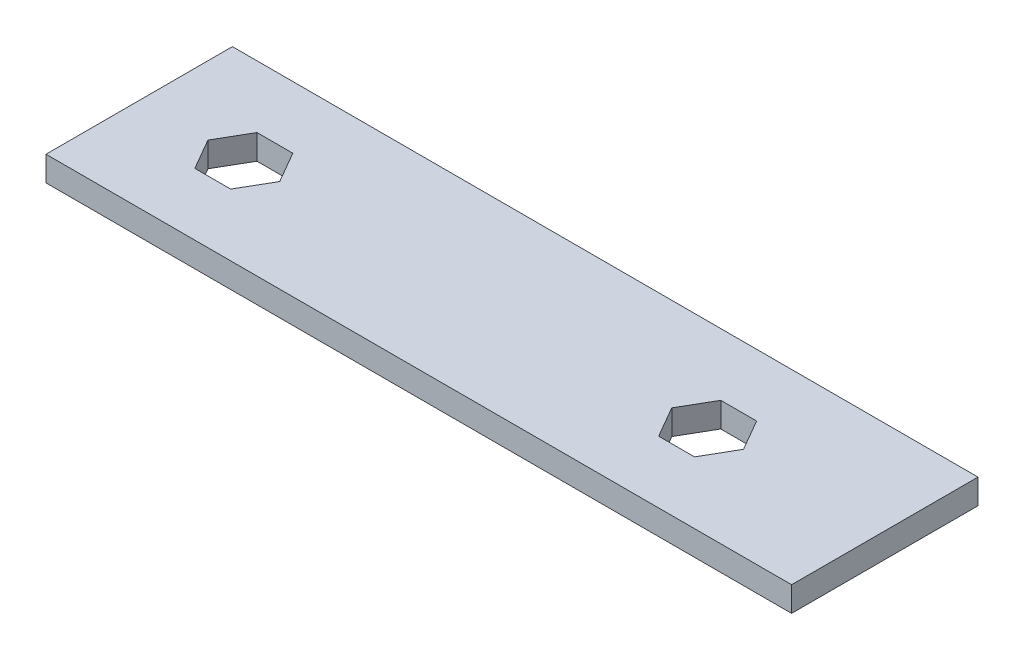
SolidWorks part; units mm, degrees
ref_plane "Front Plane" through (0, 0, 0) normal (0, 0, 1) x (1, 0, 0)
ref_plane "Top Plane" through (0, 0, 0) normal (0, 1, 0) x (1, 0, 0)
ref_plane "Right Plane" through (0, 0, 0) normal (1, 0, 0) x (0, 0, -1)
sketch "Sketch1" plane through (0, 0, 0) normal (0, 1, 0) x (1, 0, 0)
  line L1 (0, 0) -> (152.4, 0)
  line L2 (0, 0) -> (0, 38.1)
  line L3 (0, 38.1) -> (152.4, 38.1)
  line L4 (152.4, 0) -> (152.4, 38.1)
  dimension "D1" = 152.4
  dimension "D2" = 38.1
extrude "Boss-Extrude1" add sketch "Sketch1" along normal blind 5.08
sketch "Sketch2" plane through (0, 5.08, 0) normal (0, 1, 0) x (1, 0, 0)
  line L1 (25.0498, 12.7) -> (28.716, 19.05)
  line L2 (28.716, 19.05) -> (25.0498, 25.4)
  line L3 (25.0498, 25.4) -> (17.7175, 25.4)
  line L4 (17.7175, 25.4) -> (14.0513, 19.05)
  line L5 (14.0513, 19.05) -> (17.7175, 12.7)
  line L6 (17.7175, 12.7) -> (25.0498, 12.7)
  line L7 (152.4, 38.1) -> (0, 38.1) construction
  line L8 (0, 0) -> (152.4, 0) construction
  circle A0 centre (21.3836, 19.05) radius 6.35 construction
  point P10 (15.6999, 22.0742)
  dimension "D1" = 12.7
  dimension "D2" = 12.7
extrude "Cut-Extrude1" cut sketch "Sketch2" against normal through all
sketch "Sketch5" plane through (0, 5.08, 0) normal (0, 1, 0) x (1, 0, 0)
  line L1 (119.8536, 25.4) -> (112.5212, 25.4)
  line L2 (112.5212, 25.4) -> (108.855, 19.05)
  line L3 (108.855, 19.05) -> (112.5212, 12.7)
  line L4 (112.5212, 12.7) -> (119.8536, 12.7)
  line L5 (119.8536, 12.7) -> (123.5197, 19.05)
  line L6 (123.5197, 19.05) -> (119.8536, 25.4)
  line L7 (0, 0) -> (152.4, 0) construction
  line L8 (152.4, 38.1) -> (0, 38.1) construction
  line L9 (152.4, 0) -> (152.4, 38.1) construction
  circle A0 centre (116.1874, 19.05) radius 6.35 construction
  point P1 (110.6881, 15.875)
  dimension "D1" = 12.7
  dimension "D2" = 28.8803
  dimension "D3" = 12.7
extrude "Cut-Extrude3" cut sketch "Sketch5" against normal through all
